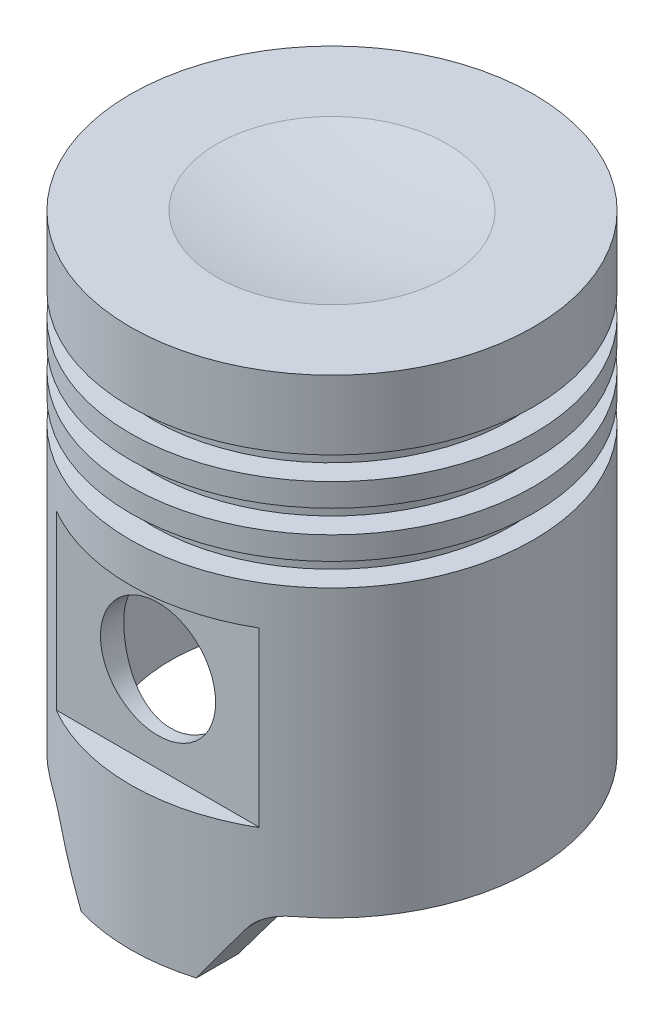
SolidWorks part; units mm, degrees
ref_plane "Front Plane" through (0, 0, 0) normal (0, 0, 1) x (1, 0, 0)
ref_plane "Top Plane" through (0, 0, 0) normal (0, 1, 0) x (1, 0, 0)
ref_plane "Right Plane" through (0, 0, 0) normal (1, 0, 0) x (0, 0, -1)
sketch "Sketch4" plane through (0, 0, 0) normal (0, 1, 0) x (1, 0, 0)
  circle A0 centre (0, 0) radius 22.225
  dimension "D1" = 44.45
extrude "Boss-Extrude1" add sketch "Sketch4" against normal blind 59.436
sketch "Sketch5" plane through (0, 0, 0) normal (0, 0, 1) x (1, 0, 0)
  line L0 (22.225, -7.62) -> (19.685, -7.62)
  line L1 (22.225, -59.436) -> (22.225, 0) construction
  line L2 (19.685, -7.62) -> (19.685, -10.16)
  line L3 (22.225, -10.16) -> (19.685, -10.16)
  line L4 (22.225, -7.62) -> (22.225, -10.16)
  line L5 (22.225, -12.7) -> (22.225, -15.24)
  line L6 (22.225, -15.24) -> (19.685, -15.24)
  line L7 (19.685, -12.7) -> (19.685, -15.24)
  line L8 (22.225, -12.7) -> (19.685, -12.7)
  line L9 (22.225, -17.78) -> (19.685, -17.78)
  line L10 (19.685, -17.78) -> (19.685, -20.32)
  line L11 (22.225, -17.78) -> (22.225, -20.32)
  line L12 (22.225, -20.32) -> (19.685, -20.32)
  line L13 (0, 26.2602) -> (0, -83.9469) construction
  dimension "D1" = 7.62
  dimension "D2" = 2.54
  dimension "0.1" = 2.54
revolve "Cut-Revolve1" cut sketch "Sketch5" angle 360 about L13
sketch "Sketch6" plane through (0, -59.436, 0) normal (0, -1, 0) x (1, 0, 0)
  circle A0 centre (0, 0) radius 17.78
  dimension "D1" = 35.56
extrude "Cut-Extrude1" cut sketch "Sketch6" against normal blind 51.816
sketch "Sketch7" plane through (0, 0, 0) normal (0, 0, 1) x (1, 0, 0)
  line L0 (0, 9.9912) -> (0, -72.0506) construction
  line L1 (22.225, -51.816) -> (13.335, -51.816)
  line L2 (22.225, -59.436) -> (22.225, -20.32) construction
  line L3 (6.35, -59.436) -> (10.2898, -53.5285)
  line L4 (22.225, -51.816) -> (22.225, -59.436)
  line L5 (58.0136, -55.626) -> (38.0994, -55.626) construction
  line L6 (36.8071, -55.6319) -> (36.6878, -55.6319) construction
  line L7 (36.6878, -55.6319) -> (13.4737, -55.6319) construction
  line L8 (13.4737, -52.3922) -> (13.4737, -60.3405) construction
  line L9 (-22.225, -59.436) -> (22.225, -59.436) construction
  line L10 (6.35, -59.436) -> (22.225, -59.436)
  line L11 (-6.35, -59.436) -> (-10.2898, -53.5285)
  line L12 (-6.35, -59.436) -> (-22.225, -59.436)
  line L13 (-22.225, -51.816) -> (-22.225, -59.436)
  line L14 (-22.225, -51.816) -> (-13.335, -51.816)
  arc A0 (-13.4595, -51.816) -> (-10.2898, -53.5285) centre (-13.4737, -55.6319) cw
  arc A1 (13.4595, -51.816) -> (10.2898, -53.5285) centre (13.4737, -55.6319) ccw
  dimension "D5" = 236.3
  dimension "D6" = 3.816
  dimension "D1" = 7.62
  dimension "D2" = 6.35
  dimension "D3" = 8.89
  dimension "D4" = 3.81
extrude "Cut-Extrude3" cut sketch "Sketch7" against normal through all both and the other way through all contours L1 A1 L3 L10 L4 | A0 L14 L13 L12 L11
ref_plane "Plane1" through (0, 0, 19.177) normal (0, 0, 1) x (1, 0, 0)
sketch "Sketch12" plane through (0, 0, 19.177) normal (0, 0, 1) x (1, 0, 0)
  line L0 (0, 8.6512) -> (0, -64.6588) construction
  line L2 (-62.113, -34.1788) -> (51.083, -34.1788) construction
  line L3 (11.176, -24.6538) -> (-11.176, -24.6538)
  line L4 (11.176, -24.6538) -> (11.176, -43.7038)
  line L5 (11.176, -43.7038) -> (-11.176, -43.7038)
  line L6 (-11.176, -24.6538) -> (-11.176, -43.7038)
  dimension "D2" = 22.352
  dimension "D1" = 19.05
extrude "Cut-Extrude5" cut sketch "Sketch12" along normal up to surface (0.0336 mm away)
sketch "Sketch13" plane through (0, 0, 19.177) normal (0, 0, 1) x (1, 0, 0)
  line L0 (-11.176, -24.6538) -> (-11.176, -43.7038) construction
  line L1 (11.176, -34.1788) -> (-11.176, -34.1788) construction
  line L3 (11.176, -43.7038) -> (11.176, -24.6538) construction
  line L4 (-11.176, -24.6538) -> (-11.176, -43.7038) construction
  line L5 (0, -24.6538) -> (0, -43.7038) construction
  line L6 (11.176, -24.6538) -> (-11.176, -24.6538) construction
  line L7 (-11.176, -43.7038) -> (11.176, -43.7038) construction
  circle A0 centre (0, -34.1788) radius 6.35
  point P0 (-11.176, -34.1788)
  point P3 (-11.176, -34.1788)
extrude "Cut-Extrude6" cut sketch "Sketch13" against normal blind 5.842
mirror "Mirror1" about plane through (0, 0, 0) normal (0, 0, 1) of "Cut-Extrude6", "Cut-Extrude5"
sketch "Sketch16" plane through (0, 0, 0) normal (0, 0, 1) x (1, 0, 0)
  line L0 (0, 0) -> (0, -1.27)
  line L1 (0, 62.992) -> (0, -65.1947) construction
  line L2 (0, 0) -> (12.7127, 0)
  arc A0 (0, -1.27) -> (12.7127, 0) centre (0, 62.992) ccw
  point P5 (0, -1.1014)
  dimension "D1" = 64.262
revolve "Cut-Revolve2" cut sketch "Sketch16" angle 360 about L1
